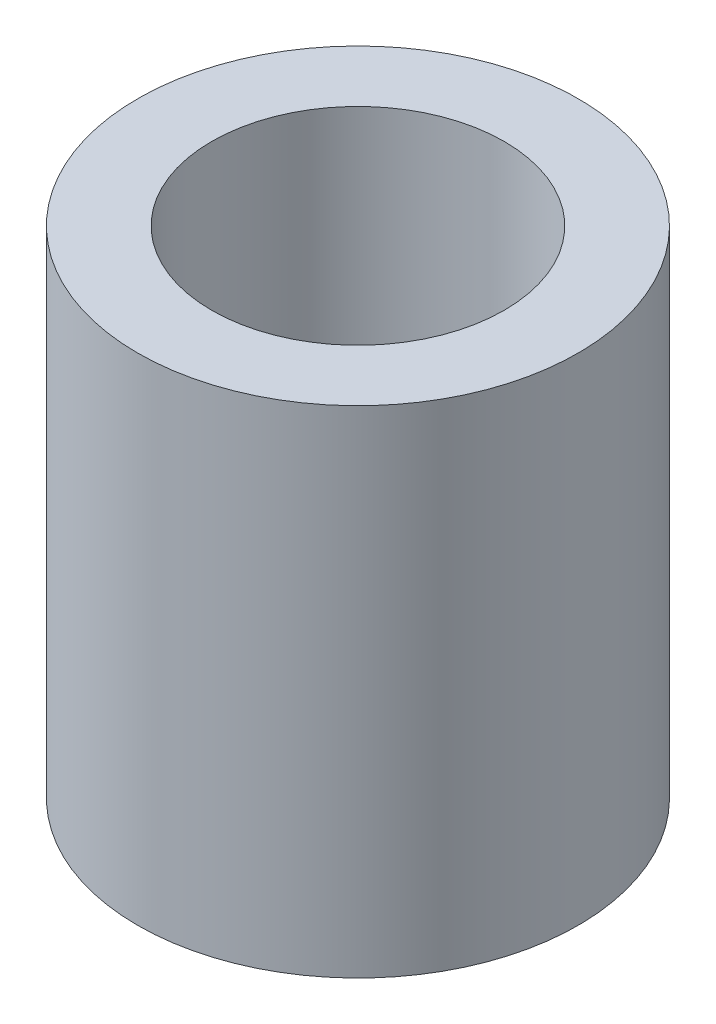
SolidWorks part; units mm, degrees
ref_plane "Front" through (0, 0, 0) normal (0, 0, 1) x (1, 0, 0)
ref_plane "Top" through (0, 0, 0) normal (0, 1, 0) x (1, 0, 0)
ref_plane "Right" through (0, 0, 0) normal (1, 0, 0) x (0, 0, -1)
sketch "Sketch1" plane through (0, 0, 0) normal (0, 1, 0) x (1, 0, 0)
  circle A0 centre (0, 0) radius 3.175
  circle A1 centre (0, 0) radius 2.1082
  dimension "D1" = 4.2164
  dimension "D2" = 6.35
extrude "Boss-Extrude1" add sketch "Sketch1" along normal blind 7.1437
ref_plane "Plane1" through (0, 3.5719, 0) normal (0, 1, 0) x (1, 0, 0)
